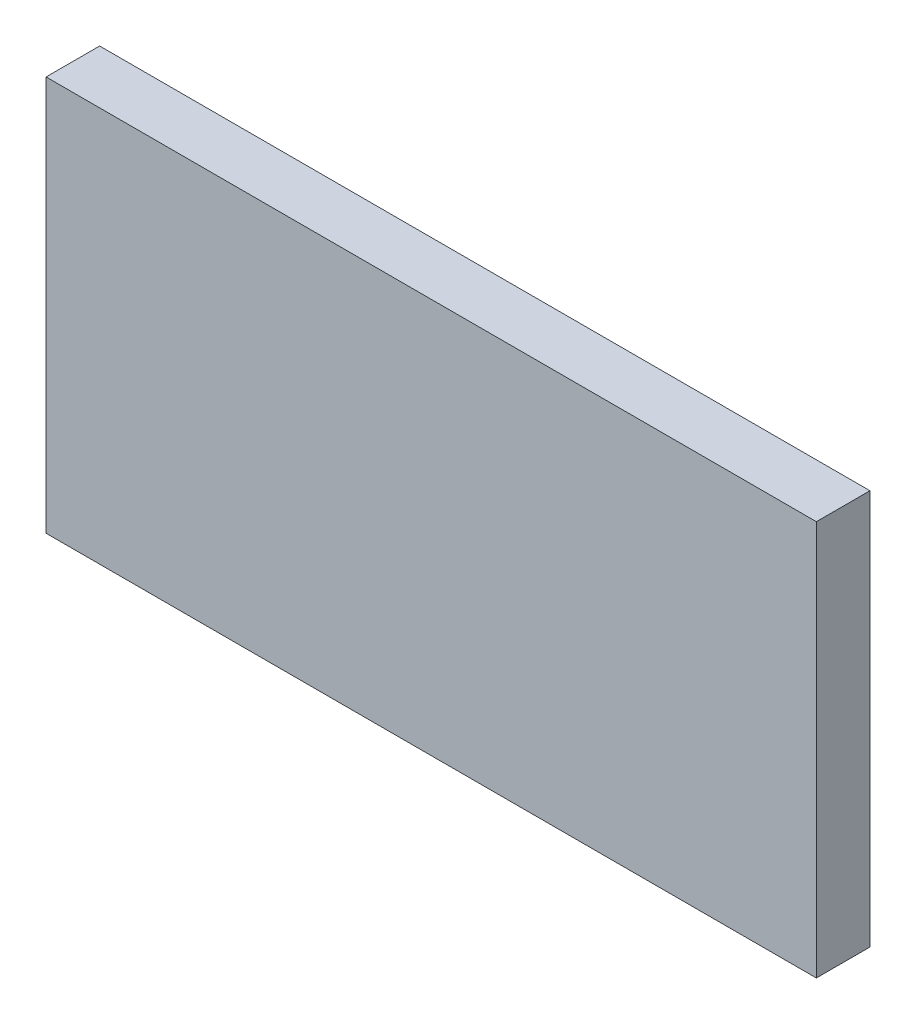
SolidWorks part; units mm, degrees
material "Q235A"
ref_plane "前视" through (0, 0, 0) normal (0, 0, 1) x (1, 0, 0)
ref_plane "上视" through (0, 0, 0) normal (0, 1, 0) x (1, 0, 0)
ref_plane "右视" through (0, 0, 0) normal (1, 0, 0) x (0, 0, -1)
sketch "草图1" plane through (0, 0, 0) normal (0, 0, 1) x (1, 0, 0)
  line L1 (115, -59) -> (-115, -59)
  line L2 (115, -59) -> (115, 59)
  line L3 (115, 59) -> (-115, 59)
  line L4 (-115, -59) -> (-115, 59)
  line L5 (115, -59) -> (-115, 59) construction
  line L6 (115, 59) -> (-115, -59) construction
  point P0 (0, 0)
  dimension "D1" = 118
  dimension "D2" = 230
extrude "凸台-拉伸1" add sketch "草图1" along normal blind 16
hole_wizard "Ø6.0 (6) 直径孔1" positions "草图3" profile "草图2" hole size "Ø6.0" standard "GB"
sketch "草图3" plane through (0, 0, 16) normal (0, 0, 1) x (1, 0, 0)
  point P0 (0, 0)
sketch "草图2" plane through (0, 0, 16) normal (1, 0, 0) x (0, -1, 0)
  line L0 (0, 0) -> (0, 29.0129)
  line L1 (0, 29.0129) -> (15, 20)
  line L2 (15, 20) -> (15, 0)
  line L5 (15, 0) -> (0, 0)
  line L10 (0, 29.0129) -> (-15, 20) construction
  line L11 (0, -6.35) -> (0, 107.95) construction
  dimension "孔直径" = 30
  dimension "孔深度" = 20
  dimension "导头角度" = 118
